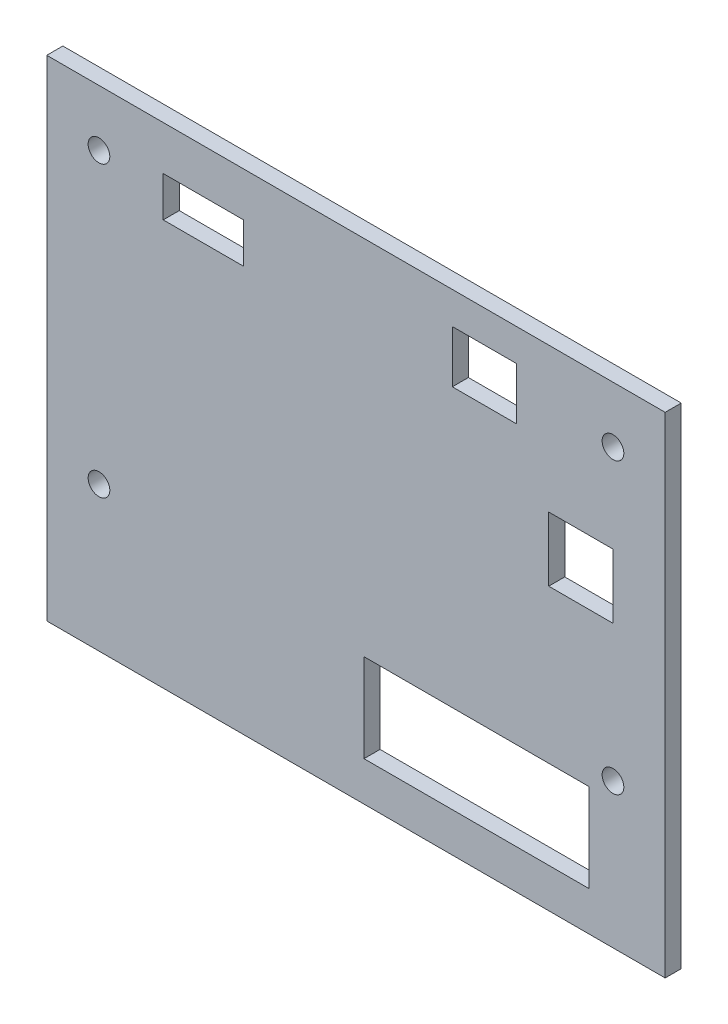
SolidWorks part; units mm, degrees
ref_plane "前视基准面" through (0, 0, 0) normal (0, 0, 1) x (1, 0, 0)
ref_plane "上视基准面" through (0, 0, 0) normal (0, 1, 0) x (1, 0, 0)
ref_plane "右视基准面" through (0, 0, 0) normal (1, 0, 0) x (0, 0, -1)
other "Configuration Table"
sketch "草图1" plane through (0, 0, 0) normal (0, 0, 1) x (1, 0, 0)
  line L1 (0, 0) -> (77, 0)
  line L2 (0, 0) -> (0, 61)
  line L3 (0, 61) -> (77, 61)
  line L4 (77, 0) -> (77, 61)
extrude "凸台-拉伸1" add sketch "草图1" along normal blind 2
sketch "草图2" plane through (0, 0, 0) normal (0, 0, 1) x (1, 0, 0)
  line L1 (39.5, 4.9) -> (67.5, 4.9)
  line L2 (39.5, 4.9) -> (39.5, 15.9)
  line L3 (39.5, 15.9) -> (67.5, 15.9)
  line L4 (67.5, 4.9) -> (67.5, 15.9)
extrude "切除-拉伸1" cut sketch "草图2" along normal through all
sketch "草图3" plane through (0, 0, 0) normal (0, 0, 1) x (1, 0, 0)
  line L1 (14.5, 50.5) -> (24.5, 50.5)
  line L2 (14.5, 50.5) -> (14.5, 55.5)
  line L3 (14.5, 55.5) -> (24.5, 55.5)
  line L4 (24.5, 50.5) -> (24.5, 55.5)
  line L5 (50.5, 50.5) -> (58.5, 50.5)
  line L6 (50.5, 50.5) -> (50.5, 57)
  line L7 (50.5, 57) -> (58.5, 57)
  line L8 (58.5, 50.5) -> (58.5, 57)
  line L9 (62.5, 35) -> (70.5, 35)
  line L10 (62.5, 35) -> (62.5, 43)
  line L11 (62.5, 43) -> (70.5, 43)
  line L12 (70.5, 35) -> (70.5, 43)
extrude "切除-拉伸2" cut sketch "草图3" along normal through all
sketch "草图4" plane through (0, 0, 0) normal (0, 0, 1) x (1, 0, 0)
  circle A0 centre (6.5, 18) radius 1.35
  circle A1 centre (70.5, 18) radius 1.35
  circle A2 centre (6.5, 54) radius 1.35
  circle A3 centre (70.5, 54) radius 1.35
extrude "切除-拉伸3" cut sketch "草图4" along normal through all
